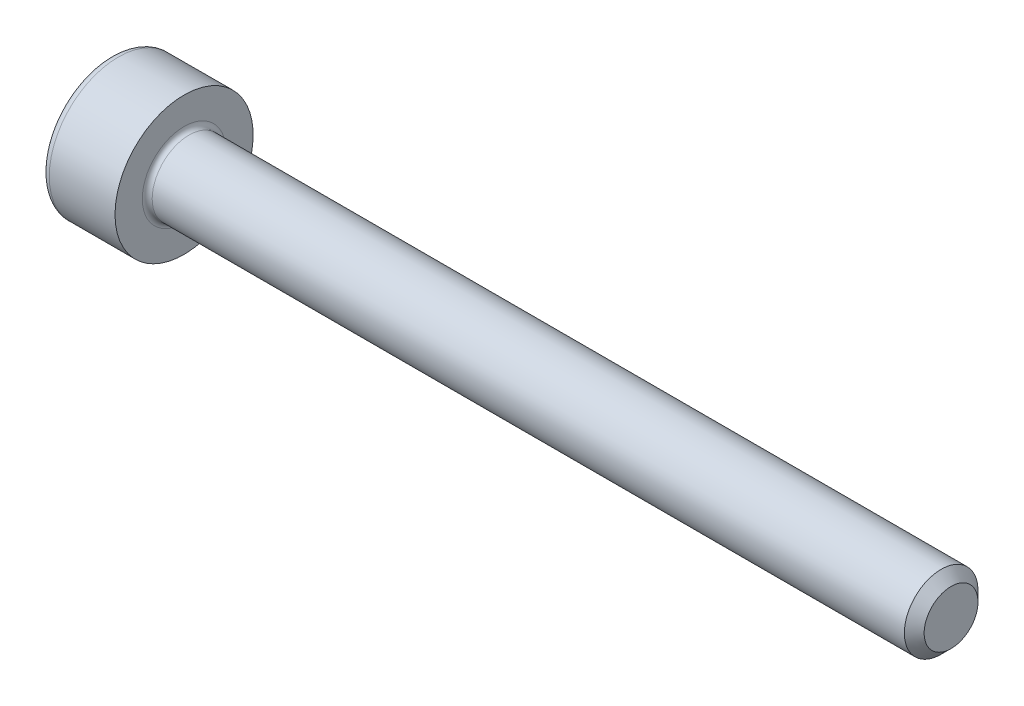
SolidWorks part; units mm, degrees
ref_plane "Спереди" through (0, 0, 0) normal (0, 0, 1) x (1, 0, 0)
ref_plane "Сверху" through (0, 0, 0) normal (0, 1, 0) x (1, 0, 0)
ref_plane "Справа" through (0, 0, 0) normal (1, 0, 0) x (0, 0, -1)
sketch "Sketch1" plane through (0, 0, 0) normal (0, 0, 1) x (1, 0, 0)
  line L0 (0, 0) -> (1.4887, 0)
  line L1 (1.4887, 0) -> (1.4887, 1.3957)
  line L2 (1.4887, 1.3957) -> (0, 1.3957)
  line L3 (0, 1.3957) -> (0, 0)
  line L4 (1.4887, 0) -> (16.9887, 0)
  line L5 (16.9887, 0) -> (16.9887, 0.7444)
  line L6 (16.9887, 0.7444) -> (1.4887, 0.7444)
  dimension "D1" = 15.5
revolve "Revolve1" add sketch "Sketch1" angle 360 about L0
fillet "Fillet1" radius 0.1 1 edges at (1.4887, 0, 0.7444)
fillet "Fillet2" radius 0.16 1 edges at (0, 0, 1.3957)
chamfer "Chamfer1" distance 0.2 angle 45 1 edges at (16.9887, 0, 0.7444)
sketch "Sketch2" plane through (0, 0, 0) normal (-1, 0, 0) x (0, 0, 1)
  line L1 (0, 0.8776) -> (-0.76, 0.4388)
  line L2 (-0.76, 0.4388) -> (-0.76, -0.4388)
  line L3 (-0.76, -0.4388) -> (0, -0.8776)
  line L4 (0, -0.8776) -> (0.76, -0.4388)
  line L5 (0.76, -0.4388) -> (0.76, 0.4388)
  line L6 (0.76, 0.4388) -> (0, 0.8776)
  circle A0 centre (0, 0) radius 0.76 construction
extrude "Extrude1" cut sketch "Sketch2" against normal blind 0.7
